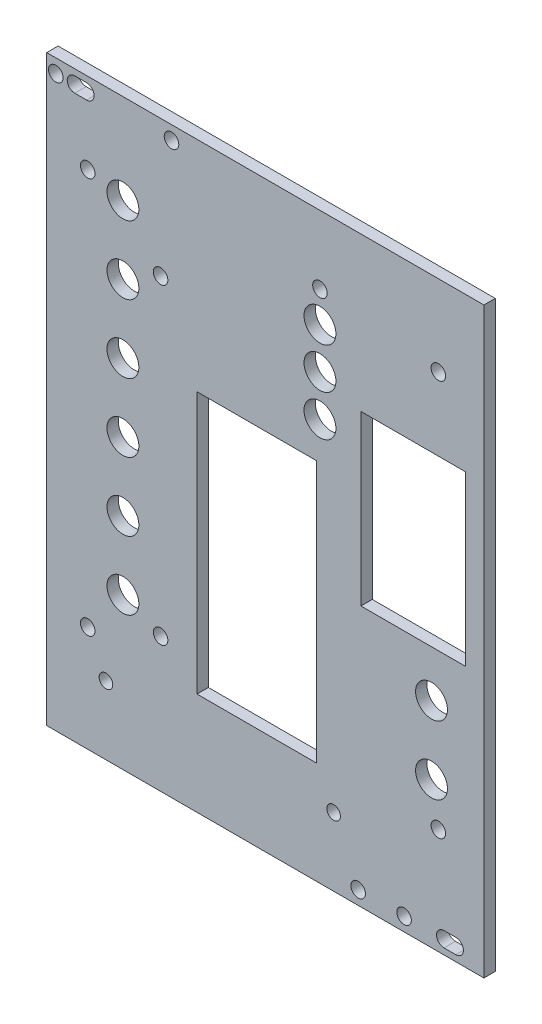
SolidWorks part; units mm, degrees
ref_plane "Front Plane" through (0, 0, 0) normal (0, 0, 1) x (1, 0, 0)
ref_plane "Top Plane" through (0, 0, 0) normal (0, 1, 0) x (1, 0, 0)
ref_plane "Right Plane" through (0, 0, 0) normal (1, 0, 0) x (0, 0, -1)
sketch "Sketch1" plane through (0, 0, 0) normal (0, 0, 1) x (1, 0, 0)
  line L1 (0, 0) -> (96, 0)
  line L2 (0, 0) -> (0, 128)
  line L3 (0, 128) -> (96, 128)
  line L4 (96, 0) -> (96, 128)
  dimension "D1" = 96
  dimension "D2" = 128
extrude "Boss-Extrude1" add sketch "Sketch1" along normal blind 2.5 contours L2 L3 L4 L1
sketch "Sketch2" plane through (0, 0, 2.5) normal (0, 0, 1) x (1, 0, 0)
  line L0 (0, 128) -> (96, 128) construction
  line L1 (0, 0) -> (96, 0) construction
  line L10 (6.15, 125) -> (8.75, 125) construction
  line L11 (6.15, 126.65) -> (8.75, 126.65)
  line L12 (6.15, 123.35) -> (8.75, 123.35)
  line L13 (87.25, 3) -> (89.85, 3) construction
  line L16 (87.25, 4.65) -> (89.85, 4.65)
  line L17 (87.25, 1.35) -> (89.85, 1.35)
  circle A0 centre (2, 125) radius 1.6
  circle A1 centre (27.4, 125) radius 1.6
  circle A2 centre (78.47, 3) radius 1.6
  circle A3 centre (68.39, 3) radius 1.6
  arc A4 (6.15, 126.65) -> (6.15, 123.35) centre (6.15, 125) ccw
  arc A5 (8.75, 123.35) -> (8.75, 126.65) centre (8.75, 125) ccw
  arc A8 (87.25, 4.65) -> (87.25, 1.35) centre (87.25, 3) ccw
  arc A9 (89.85, 1.35) -> (89.85, 4.65) centre (89.85, 3) ccw
  point P4 (7.45, 125)
  point P12 (0, 0)
  point P13 (85.6, 3)
  point P14 (91.5, 3)
  point P15 (10.4, 125)
  point P16 (4.5, 125)
  point P28 (88.55, 3)
  point P33 (0, 0)
  dimension "D1" = 3.2
  dimension "D2" = 2
  dimension "D3" = 3
  dimension "D8" = 3.2
  dimension "D15" = 3.2
  dimension "D16" = 3.2
  dimension "D17" = 10.08
  dimension "D19" = 3
  dimension "D20" = 3
  dimension "D4" = 7.45
  dimension "D5" = 3
  dimension "D6" = 3
  dimension "D7" = 7.45
  dimension "D9" = 25.4
  dimension "D10" = 3
  dimension "D11" = 5.9
  dimension "D12" = 2.6
  dimension "D13" = 5.9
  dimension "D14" = 2.6
  dimension "D18" = 10.08
extrude "Cut-Extrude1" cut sketch "Sketch2" against normal through all
sketch "Sketch3" plane through (0, 0, 2.5) normal (0, 0, 1) x (1, 0, 0)
  line L0 (0, 128) -> (96, 128) construction
  line L1 (0, 0) -> (0, 128) construction
  circle A0 centre (25, 98) radius 1.6
  circle A1 centre (60, 113) radius 1.6
  circle A2 centre (25, 29.5) radius 1.6
  dimension "D1" = 3.2
  dimension "D2" = 30
  dimension "D3" = 25
  dimension "D4" = 3.2
  dimension "D5" = 15
  dimension "D6" = 60
  dimension "D7" = 3.2
  dimension "D8" = 68.5
  dimension "D9" = 25
extrude "Cut-Extrude2" cut sketch "Sketch3" against normal through all
sketch "Sketch4" plane through (0, 0, 2.5) normal (0, 0, 1) x (1, 0, 0)
  line L0 (0, 0) -> (96, 0) construction
  line L1 (0, 0) -> (0, 128) construction
  circle A0 centre (13, 15) radius 1.5
  circle A1 centre (63, 15) radius 1.5
  dimension "D1" = 3
  dimension "D3" = 13
  dimension "D4" = 3
  dimension "D5" = 50
  dimension "D6" = 15
  dimension "D2" = 15
extrude "Cut-Extrude3" cut sketch "Sketch4" against normal through all
sketch "Sketch5" plane through (0, 0, 2.5) normal (0, 0, 1) x (1, 0, 0)
  line L0 (0, 128) -> (96, 128) construction
  line L1 (23.5, 116.25) -> (28.3, 116.25)
  line L2 (23.5, 116.25) -> (23.5, 11.25)
  line L3 (23.5, 11.25) -> (28.3, 11.25)
  line L4 (28.3, 116.25) -> (28.3, 11.25)
  line L5 (32, 113.75) -> (33.6, 113.75)
  line L6 (32, 113.75) -> (32, 13.75)
  line L7 (32, 13.75) -> (33.6, 13.75)
  line L8 (33.6, 113.75) -> (33.6, 13.75)
  line L9 (66, 116.25) -> (69.5, 116.25)
  line L10 (66, 116.25) -> (66, 11.25)
  line L11 (66, 11.25) -> (69.5, 11.25)
  line L12 (69.5, 116.25) -> (69.5, 11.25)
  circle A0 centre (25, 98) radius 1.6 construction
  circle A1 centre (37.5477, 124.5) radius 1.6
  circle A2 centre (27.4, 125) radius 1.6 construction
  dimension "D3" = 3.3
  dimension "D4" = 18.25
  dimension "D5" = 1.6
  dimension "D13" = 3.2
  dimension "D1" = 105
  dimension "D2" = 4.8
  dimension "D6" = 8.5
  dimension "D7" = 100
  dimension "D8" = 2.5
  dimension "D9" = 3.5
  dimension "D10" = 105
  dimension "D11" = 11.75
  dimension "D12" = 46
  dimension "D14" = 3.5
  dimension "D15" = 10.16
sketch "Sketch9" plane through (0, 0, 2.5) normal (0, 0, 1) x (1, 0, 0)
  line L0 (0, 0) -> (0, 128) construction
  line L1 (0, 128) -> (96, 128) construction
  circle A0 centre (9, 110.25) radius 1.6
  circle A1 centre (9, 23.25) radius 1.6
  circle A2 centre (86, 23.25) radius 1.6
  circle A3 centre (86, 110.25) radius 1.6
  dimension "D1" = 3.2
  dimension "D4" = 3.2
  dimension "D7" = 3.2
  dimension "D9" = 3.2
  dimension "D10" = 77
  dimension "D11" = 87
  dimension "D12" = 17.75
  dimension "D2" = 9
  dimension "D3" = 17.75
  dimension "D5" = 9
  dimension "D6" = 87
  dimension "D8" = 77
extrude "Cut-Extrude4" cut sketch "Sketch9" against normal through all
sketch "Sketch12" plane through (0, 0, 2.5) normal (0, 0, 1) x (1, 0, 0)
  circle A0 centre (16.73, 108.25) radius 3.5
  circle A1 centre (9, 110.25) radius 1.6 construction
  circle A2 centre (16.8063, 108.1554) radius 3.5
  circle A3 centre (16.73, 93.25) radius 3.5
  circle A4 centre (0, 0) radius 3.5
  circle A5 centre (16.73, 78.25) radius 3.5
  circle A6 centre (16.73, 63.25) radius 3.5
  circle A7 centre (16.73, 48.25) radius 3.5
  circle A8 centre (16.73, 33.25) radius 3.5
  circle A9 centre (16.7681, 93.2027) radius 3.5
  circle A10 centre (16.6919, 78.2973) radius 3.5
  circle A11 centre (16.6919, 63.2973) radius 3.5
  circle A12 centre (60, 106.25) radius 3.5
  circle A13 centre (60, 88.25) radius 3.5
  circle A14 centre (60, 97.25) radius 3.5
  circle A15 centre (60, 113) radius 1.6 construction
  circle A16 centre (84.5, 32) radius 3.5
  circle A17 centre (84.5, 47) radius 3.5
  circle A18 centre (86, 23.25) radius 1.6 construction
  point P4 (0, 0)
  point P33 (0, 0)
  dimension "D1" = 7
  dimension "D2" = 7.73
  dimension "D5" = 7.73
  dimension "D6" = 7
  dimension "D9" = 15
  dimension "D11" = 7
  dimension "D12" = 7
  dimension "D13" = 7.73
  dimension "D14" = 7
  dimension "D18" = 7
  dimension "D22" = 0
  dimension "D23" = 0
  dimension "D25" = 7
  dimension "D26" = 7
  dimension "D27" = 7
  dimension "D3" = 2
  dimension "D4" = 15
  dimension "D7" = 15
  dimension "D8" = 7.73
  dimension "D10" = 7.73
  dimension "D15" = 15
  dimension "D16" = 15
  dimension "D17" = 7.73
  dimension "D19" = 6.75
  dimension "D20" = 9
  dimension "D21" = 9
  dimension "D24" = 0
  dimension "D28" = 8.75
  dimension "D29" = 15
  dimension "D30" = 1.5
extrude "Cut-Extrude5" cut sketch "Sketch12" against normal through all contours A0 | A3 | A5 | A6 | A7 | A8 | A16 | A17 | A13 | A14 | A12
sketch "Sketch13" plane through (0, 0, 2.5) normal (0, 0, 1) x (1, 0, 0)
  line L1 (69, 94.25) -> (92, 94.25)
  line L2 (69, 94.25) -> (69, 57.25)
  line L3 (69, 57.25) -> (92, 57.25)
  line L4 (92, 94.25) -> (92, 57.25)
  line L5 (33, 22.5) -> (59.25, 22.5)
  line L6 (33, 22.5) -> (33, 80)
  line L7 (33, 80) -> (59.25, 80)
  line L8 (59.25, 22.5) -> (59.25, 80)
  circle A0 centre (86, 110.25) radius 1.6 construction
  circle A1 centre (9, 23.25) radius 1.6 construction
  dimension "D4" = 6
  dimension "D1" = 37
  dimension "D2" = 23
  dimension "D3" = 16
  dimension "D5" = 57.5
  dimension "D6" = 26.25
  dimension "D7" = 24
  dimension "D8" = 0.75
extrude "Cut-Extrude6" cut sketch "Sketch13" against normal through all
